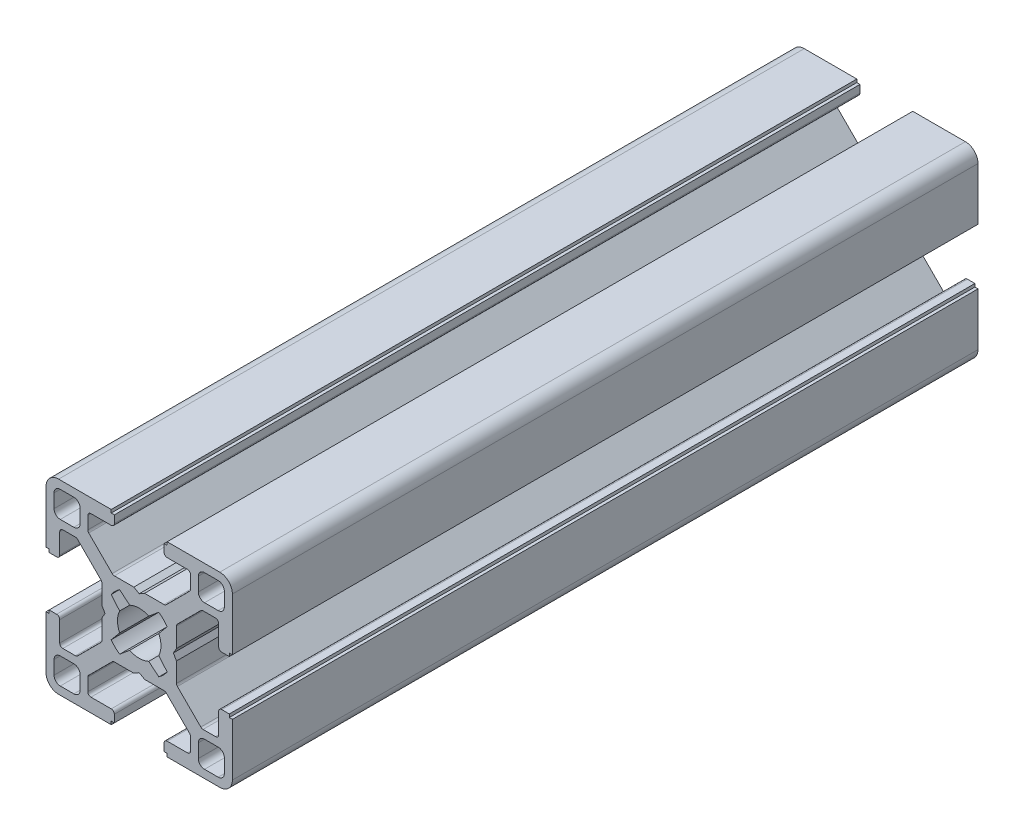
SolidWorks part; units mm, degrees
ref_plane "Front Plane" through (0, 0, 0) normal (0, 0, 1) x (1, 0, 0)
ref_plane "Top Plane" through (0, 0, 0) normal (0, 1, 0) x (1, 0, 0)
ref_plane "Right Plane" through (0, 0, 0) normal (1, 0, 0) x (0, 0, -1)
sketch "Sketch1" plane through (0, 0, 0) normal (0, 0, 1) x (1, 0, 0)
  line L0 (-15, 0) -> (15, 0) construction
  line L1 (0, -15) -> (0, 15) construction
  line L2 (-4.5, 15) -> (4.5, 15) construction
  line L3 (-4, -15) -> (4, -15) construction
  line L4 (-4.5, 15) -> (-4.5, 14.5)
  line L5 (-4.5, 14.5) -> (-4, 14.5)
  line L6 (-4, 14.5) -> (-4, 13.29)
  line L7 (-4.5, 12.79) -> (-7.7675, 12.79)
  line L8 (-8.2675, 12.29) -> (-8.2675, 10.2707)
  line L9 (-8.1211, 9.9171) -> (-4.3504, 6.1464)
  line L10 (-3.9968, 6) -> (0, 6)
  line L11 (0, 0) -> (-15, 15) construction
  line L12 (-4.5, 15) -> (-12.968, 15)
  line L14 (-12.705, 9.5135) -> (-10.5135, 9.5135)
  line L15 (-13.705, 10.5135) -> (-13.705, 12.705)
  line L16 (-12.705, 13.705) -> (-10.5135, 13.705)
  line L17 (-9.5135, 10.5135) -> (-9.5135, 12.705)
  line L18 (-13.705, 9.5135) -> (-9.5135, 13.705) construction
  line L19 (-13.705, 13.705) -> (-9.5135, 9.5135) construction
  line L20 (-3.1568, 4.5038) -> (-1.5303, 3.1477) construction
  line L21 (-4.5038, 3.1568) -> (-3.1477, 1.5303) construction
  line L22 (-6, 3.9968) -> (-6, 0)
  line L23 (-9.9171, 8.1211) -> (-6.1464, 4.3504)
  line L24 (-15, 4.5) -> (-15, 12.968)
  line L25 (-12.29, 8.2675) -> (-10.2707, 8.2675)
  line L26 (-12.79, 4.5) -> (-12.79, 7.7675)
  line L27 (-14.5, 4) -> (-13.29, 4)
  line L28 (-14.5, 4.5) -> (-14.5, 4)
  line L29 (-15, 4.5) -> (-14.5, 4.5)
  circle A0 centre (0, 0) radius 3.5
  arc A1 (-12.968, 15) -> (-15, 12.968) centre (-12.968, 12.968) ccw
  circle A2 centre (0, 0) radius 5.5 construction
  arc A3 (-10.5135, 9.5135) -> (-9.5135, 10.5135) centre (-10.5135, 10.5135) ccw
  arc A4 (-13.705, 12.705) -> (-12.705, 13.705) centre (-12.705, 12.705) cw
  arc A5 (-10.5135, 13.705) -> (-9.5135, 12.705) centre (-10.5135, 12.705) cw
  arc A6 (-12.705, 9.5135) -> (-13.705, 10.5135) centre (-12.705, 10.5135) cw
  arc A7 (-12.79, 4.5) -> (-13.29, 4) centre (-13.29, 4.5) cw
  arc A8 (-12.29, 8.2675) -> (-12.79, 7.7675) centre (-12.29, 7.7675) ccw
  arc A9 (-9.9171, 8.1211) -> (-10.2707, 8.2675) centre (-10.2707, 7.7675) ccw
  arc A10 (-6, 3.9968) -> (-6.1464, 4.3504) centre (-6.5, 3.9968) ccw
  arc A11 (-4.3504, 6.1464) -> (-3.9968, 6) centre (-3.9968, 6.5) ccw
  arc A12 (-4, 13.29) -> (-4.5, 12.79) centre (-4.5, 13.29) cw
  arc A13 (-7.7675, 12.79) -> (-8.2675, 12.29) centre (-7.7675, 12.29) ccw
  arc A14 (-8.2675, 10.2707) -> (-8.1211, 9.9171) centre (-7.7675, 10.2707) ccw
  point P4 (0, 0)
  point P8 (0, 0)
  point P13 (0, 15)
  point P15 (0, -15)
  point P16 (0, 6)
  point P23 (-11.6092, 11.6093)
  point P26 (0, 6)
  point P62 (-12.79, 4)
  point P65 (-12.79, 8.2675)
  point P68 (-10.0636, 8.2675)
  point P71 (-6, 4.2039)
  point P74 (-4.2039, 6)
  point P77 (-4, 12.79)
  point P80 (-8.2675, 12.79)
  point P83 (-8.2675, 10.0636)
  dimension "Center Hole Diameter" = 7
  dimension "D11" = 2.032
  dimension "D9" = 11
  dimension "D13" = 1
  dimension "D14" = 0.5
  dimension "Rail Height" = 30
  dimension "Rail Width" = 30
  dimension "T-Slot Width" = 8
  dimension "T-Slot Depth" = 9
  dimension "D1" = 9
  dimension "D2" = 45
  dimension "D3" = 8
  dimension "D4" = 2.21
  dimension "D5" = 16.535
  dimension "D7" = 2.54
  dimension "D6" = 1.295
  dimension "D8" = 1.246
  dimension "D10" = 10.36
  dimension "D12" = 1.905
sketch "Sketch2" plane through (0, 0, 0) normal (1, 0, 0) x (0, 0, -1)
  line L0 (-76.2, 0) -> (76.2, 0) construction
  line L2 (0, -15) -> (0, 15) construction
  line L3 (0, -15) -> (0, 15) construction
  line L4 (-76.2, -15) -> (-76.2, 15) construction
  line L5 (76.2, -15) -> (76.2, 15) construction
  point P0 (-38.7, 0)
  point P3 (0, 0)
  point P4 (38.7, 0)
  point P12 (-76.2, 0)
  point P14 (76.2, 0)
  dimension "Length" = 152.4
  dimension "D1" = 37.5
sketch "Sketch3" plane through (0, 0, 0) normal (0, 0, 1) x (1, 0, 0)
  line L0 (-4.5038, 3.1568) -> (-3.1477, 1.5303)
  line L1 (0, 3.5) -> (0, 5.5)
  line L2 (-5.5, 0) -> (-3.5, 0)
  line L7 (-6, 3.9968) -> (-6, 0) construction
  line L31 (-9.9171, 8.1211) -> (-6.1464, 4.3504) construction
  line L117 (-12.29, 8.2675) -> (-10.2707, 8.2675) construction
  line L118 (-12.79, 4.5) -> (-12.79, 7.7675) construction
  line L157 (-12.705, 9.5135) -> (-10.5135, 9.5135)
  line L158 (-9.5135, 10.5135) -> (-9.5135, 12.705)
  line L163 (-10.5135, 13.705) -> (-12.705, 13.705)
  line L164 (-13.705, 12.705) -> (-13.705, 10.5135)
  line L165 (-12.705, 9.5135) -> (-10.5135, 9.5135)
  line L166 (-9.5135, 10.5135) -> (-9.5135, 12.705)
  line L167 (-10.5135, 13.705) -> (-12.705, 13.705)
  line L168 (-13.705, 12.705) -> (-13.705, 10.5135)
  line L169 (-14.5, 4) -> (-13.29, 4) construction
  line L170 (-14.5, 4.5) -> (-14.5, 4) construction
  line L171 (-15, 4.5) -> (-14.5, 4.5) construction
  line L172 (-15, 4.5) -> (-15, 12.968) construction
  line L173 (-4.5, 15) -> (-12.968, 15) construction
  line L174 (-4.5, 15) -> (-4.5, 14.5) construction
  line L175 (-4.5, 14.5) -> (-4, 14.5) construction
  line L176 (-4, 14.5) -> (-4, 13.29) construction
  line L177 (-4.5, 12.79) -> (-7.7675, 12.79) construction
  line L178 (-8.2675, 12.29) -> (-8.2675, 10.2707) construction
  line L179 (-8.1211, 9.9171) -> (-4.3504, 6.1464) construction
  line L180 (-3.9968, 6) -> (0, 6) construction
  line L181 (-6, 3.9968) -> (-6, 0.866)
  line L182 (-9.9171, 8.1211) -> (-6.1464, 4.3504)
  line L183 (-12.29, 8.2675) -> (-10.2707, 8.2675)
  line L184 (-12.79, 4.5) -> (-12.79, 7.7675)
  line L185 (-14.5, 4) -> (-13.29, 4)
  line L186 (-14.5, 4.5) -> (-14.5, 4)
  line L187 (-15, 4.5) -> (-14.5, 4.5)
  line L188 (-15, 4.5) -> (-15, 12.968)
  line L189 (-4.5, 15) -> (-12.968, 15)
  line L190 (-4.5, 15) -> (-4.5, 14.5)
  line L191 (-4.5, 14.5) -> (-4, 14.5)
  line L192 (-4, 14.5) -> (-4, 13.29)
  line L193 (-4.5, 12.79) -> (-7.7675, 12.79)
  line L194 (-8.2675, 12.29) -> (-8.2675, 10.2707)
  line L195 (-8.1211, 9.9171) -> (-4.3504, 6.1464)
  line L196 (-3.9968, 6) -> (-0.866, 6)
  line L197 (-0.866, 6) -> (0, 5.5)
  line L198 (0, -15) -> (0, 15) construction
  line L199 (0, 0) -> (-15, 15) construction
  line L200 (0, 0) -> (-15, 15) construction
  line L201 (-3.1568, 4.5038) -> (-1.5303, 3.1477) construction
  line L202 (-3.1568, 4.5038) -> (-1.5303, 3.1477)
  line L203 (-6, 0.866) -> (-5.5, 0)
  line L204 (-15, 0) -> (15, 0) construction
  line L205 (-15, 0) -> (15, 0) construction
  line L206 (0, -15) -> (0, 15) construction
  arc A0 (-3.5, 0) -> (-3.1477, 1.5303) centre (0, 0) cw
  arc A10 (-6, 3.9968) -> (-6.1464, 4.3504) centre (-6.5, 3.9968) ccw construction
  circle A16 centre (0, 0) radius 3.5
  arc A18 (0, 3.5) -> (-1.5303, 3.1477) centre (0, 0) ccw
  arc A20 (-9.9171, 8.1211) -> (-10.2707, 8.2675) centre (-10.2707, 7.7675) ccw construction
  arc A22 (-12.29, 8.2675) -> (-12.79, 7.7675) centre (-12.29, 7.7675) ccw construction
  arc A28 (-13.29, 4) -> (-12.79, 4.5) centre (-13.29, 4.5) ccw construction
  arc A29 (-10.5135, 9.5135) -> (-9.5135, 10.5135) centre (-10.5135, 10.5135) ccw
  arc A30 (-9.5135, 12.705) -> (-10.5135, 13.705) centre (-10.5135, 12.705) ccw
  arc A31 (-12.705, 13.705) -> (-13.705, 12.705) centre (-12.705, 12.705) ccw
  arc A32 (-13.705, 10.5135) -> (-12.705, 9.5135) centre (-12.705, 10.5135) ccw
  arc A33 (-10.5135, 9.5135) -> (-9.5135, 10.5135) centre (-10.5135, 10.5135) ccw
  arc A34 (-9.5135, 12.705) -> (-10.5135, 13.705) centre (-10.5135, 12.705) ccw
  arc A35 (-12.705, 13.705) -> (-13.705, 12.705) centre (-12.705, 12.705) ccw
  arc A36 (-13.705, 10.5135) -> (-12.705, 9.5135) centre (-12.705, 10.5135) ccw
  arc A37 (-12.968, 15) -> (-15, 12.968) centre (-12.968, 12.968) ccw construction
  arc A38 (-4.5, 12.79) -> (-4, 13.29) centre (-4.5, 13.29) ccw construction
  arc A39 (-7.7675, 12.79) -> (-8.2675, 12.29) centre (-7.7675, 12.29) ccw construction
  arc A40 (-8.2675, 10.2707) -> (-8.1211, 9.9171) centre (-7.7675, 10.2707) ccw construction
  arc A41 (-4.3504, 6.1464) -> (-3.9968, 6) centre (-3.9968, 6.5) ccw construction
  arc A42 (-6, 3.9968) -> (-6.1464, 4.3504) centre (-6.5, 3.9968) ccw
  arc A43 (-9.9171, 8.1211) -> (-10.2707, 8.2675) centre (-10.2707, 7.7675) ccw
  arc A44 (-12.29, 8.2675) -> (-12.79, 7.7675) centre (-12.29, 7.7675) ccw
  arc A45 (-13.29, 4) -> (-12.79, 4.5) centre (-13.29, 4.5) ccw
  arc A46 (-12.968, 15) -> (-15, 12.968) centre (-12.968, 12.968) ccw
  arc A47 (-4.5, 12.79) -> (-4, 13.29) centre (-4.5, 13.29) ccw
  arc A48 (-7.7675, 12.79) -> (-8.2675, 12.29) centre (-7.7675, 12.29) ccw
  arc A49 (-8.2675, 10.2707) -> (-8.1211, 9.9171) centre (-7.7675, 10.2707) ccw
  arc A50 (-4.3504, 6.1464) -> (-3.9968, 6) centre (-3.9968, 6.5) ccw
  circle A51 centre (0, 0) radius 5.5 construction
  arc A52 (-3.1568, 4.5038) -> (-4.5038, 3.1568) centre (0, 0) ccw
  dimension "D3" = 60
  dimension "D4" = 60
  dimension "D1" = 0
  dimension "D2" = 0
extrude "Boss-Extrude1" add sketch "Sketch3" along normal mid plane 120
pattern_circular "CirPattern1" count 4 over 360 about axis through (0, 0, 0) along (0, 0, 1) of "Boss-Extrude1"
ref_plane "Contact Plane1" through (15, 0, 0) normal (1, 0, 0) x (0, 0, -1)
ref_plane "Contact Plane2" through (0, -15, 0) normal (0, 1, 0) x (1, 0, 0)
ref_plane "Contact Plane3" through (-15, 0, 0) normal (1, 0, 0) x (0, 0, -1)
ref_plane "Contact Plane4" through (0, 15, 0) normal (0, 1, 0) x (1, 0, 0)
equation "\"D1@Sketch2\" = \"Rail Height@Sketch1\" * 1.25"
equation "\"D1@Sketch1\"=\"T-Slot Width@Sketch1\"+1mm"
equation "\"D3@Sketch1\"=\"T-Slot Width@Sketch1\""
equation "\"D1@Boss-Extrude1\"=\"Width\""
equation "\"Width\" = 120mm"
